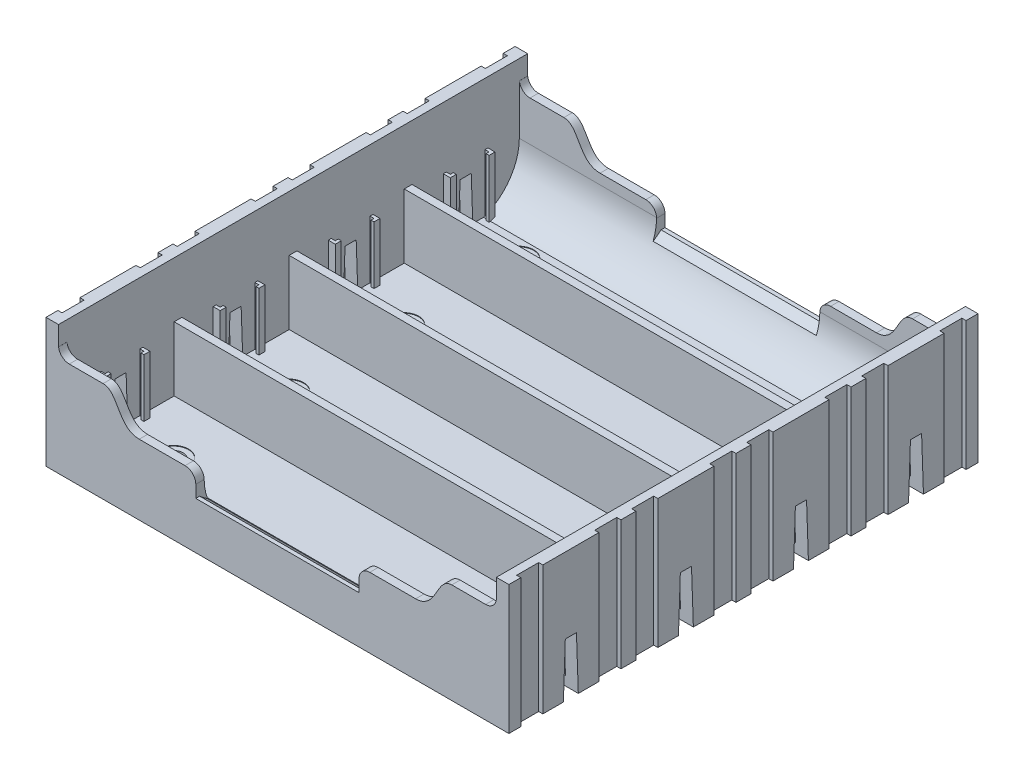
SolidWorks part; units mm, degrees
ref_plane "Спереди" through (0, 0, 0) normal (0, 0, 1) x (1, 0, 0)
ref_plane "Сверху" through (0, 0, 0) normal (0, 1, 0) x (1, 0, 0)
ref_plane "Справа" through (0, 0, 0) normal (1, 0, 0) x (0, 0, -1)
sketch "Эскиз1" plane through (0, 0, 0) normal (0, 0, 1) x (1, 0, 0)
  line L0 (-36.725, 0) -> (36.725, 0)
  line L1 (-36.725, 0) -> (-36.725, 18.61)
  line L2 (-36.725, 18.61) -> (-34.925, 18.61) construction
  line L3 (-34.925, 16.81) -> (-29.245, 16.81)
  line L4 (-23.185, 11.76) -> (-15.495, 11.76)
  line L5 (-15.495, 11.76) -> (-15.495, 9.96) construction
  line L6 (-13.695, 9.96) -> (-13.695, 7.9)
  line L7 (-13.695, 7.9) -> (13.695, 7.9)
  line L8 (0, 7.9) -> (0, 0) construction
  line L9 (36.725, 0) -> (36.725, 18.61)
  line L10 (34.925, 16.81) -> (29.245, 16.81)
  line L11 (23.185, 11.76) -> (15.495, 11.76)
  line L12 (13.695, 9.96) -> (13.695, 7.9)
  arc A0 (-36.725, 18.61) -> (-34.925, 16.81) centre (-34.925, 18.61) ccw
  arc A1 (-15.495, 11.76) -> (-13.695, 9.96) centre (-15.495, 9.96) cw
  arc A2 (36.725, 18.61) -> (34.925, 16.81) centre (34.925, 18.61) cw
  arc A3 (15.495, 11.76) -> (13.695, 9.96) centre (15.495, 9.96) ccw
  spline S0 degree 3 poles (-29.245, 16.81) (-26.6157, 16.7858) (-26.8128, 11.7896) (-23.185, 11.76) knots 0 0 0 0 1 1 1 1
  spline S1 degree 3 poles (29.245, 16.81) (26.6157, 16.7858) (26.8128, 11.7896) (23.185, 11.76) knots 0 0 0 0 1 1 1 1
  point P4 (0, 0)
  dimension "D1" = 73.45
  dimension "D2" = 18.61
  dimension "D3" = 1.8
  dimension "D4" = 5.68
  dimension "D5" = 7.69
  dimension "D6" = 5.05
  dimension "D7" = 6.06
  dimension "D8" = 1.8
  dimension "D9" = 2.06
extrude "Бобышка-Вытянуть1" add sketch "Эскиз1" against normal blind 10.4
sketch "Эскиз2" plane through (-36.725, 0, 0) normal (-1, 0, 0) x (0, 0, 1)
  line L5 (0, 18.61) -> (0, 0) construction
  line L42 (0, 1.5749) -> (-3, 1.5749)
  line L43 (-3, -0.9251) -> (-3, 1.5749) construction
  line L44 (-9, 10.0602) -> (-9, 18.4052)
  line L45 (-9, 18.4052) -> (-10.7657, 18.4052)
  line L46 (-10.7657, 18.4052) -> (-10.7657, 19.9735)
  line L47 (-10.7657, 19.9735) -> (0, 19.9735)
  line L48 (0, 19.9735) -> (0, 1.5749)
  arc A3 (-9, 10.0602) -> (-3, 1.5749) centre (0, 10.0602) ccw
  dimension "D1" = 3
  dimension "D3" = 9
  dimension "D2" = 2.5
  dimension "D5" = 3
extrude "Вырез-Вытянуть1" cut sketch "Эскиз2" against normal through all
sketch "Эскиз3" plane through (-36.725, 0, 0) normal (-1, 0, 0) x (0, 0, 1)
  line L0 (0, 0) -> (-10.4, 0) construction
  line L1 (0, 0) -> (0, 19.1837) construction
  line L3 (-10.4, 0) -> (-5.2, 0) construction
  circle A0 centre (0, 19.3) radius 15
  dimension "D1" = 19.3
extrude "Вырез-Вытянуть2" cut sketch "Эскиз3" against normal up to surface (27.39 mm away) from surface at -23.03 contours A0 up to face at (13.695, 8.9281, -9.649) starting at face at (-13.695, 8.9281, -9.649)
mirror "Зеркальное отражение6" [suppressed]
sketch "Эскиз4" plane through (0, 0, 0) normal (0, -1, 0) x (1, 0, 0)
  line L0 (36.725, 0) -> (-36.725, 0) construction
  line L8 (-36.05, -3.25) -> (-36.05, -2.75) construction
  line L9 (36.05, 2.75) -> (36.05, 3.25) construction
  line L10 (36.05, -3.25) -> (36.05, -2.75) construction
  line L11 (36.725, -10.4) -> (36.725, 0) construction
  line L12 (-36.05, -3.25) -> (-37.25, -3.25)
  line L13 (-36.05, -3.25) -> (-36.05, -2.75)
  line L14 (-36.05, 3.25) -> (-37.25, 3.25)
  line L17 (36.05, 2.75) -> (36.05, 3.25)
  line L18 (-35.55, -3.75) -> (-35.55, -2.75)
  line L19 (-37.25, 3.75) -> (-35.55, 3.75)
  line L21 (-37.25, -3.75) -> (-35.55, -3.75)
  line L23 (37.25, -3.75) -> (37.25, -3.25)
  line L24 (35.55, -2.75) -> (36.05, -2.75)
  line L25 (-35.55, 3.75) -> (-35.55, 2.75)
  line L26 (-37.25, 3.25) -> (-37.25, 3.75)
  line L27 (-35.55, 2.75) -> (-36.05, 2.75)
  line L28 (-35.55, -2.75) -> (-36.05, -2.75)
  line L29 (-37.25, -3.75) -> (-37.25, -3.25)
  line L31 (-36.05, 2.75) -> (-36.05, 3.25)
  line L32 (-36.05, 2.75) -> (-36.05, 3.25) construction
  line L33 (35.55, 2.75) -> (36.05, 2.75)
  line L34 (37.25, 3.25) -> (37.25, 3.75)
  line L35 (35.55, 3.75) -> (35.55, 2.75)
  line L36 (37.25, -3.75) -> (35.55, -3.75)
  line L37 (37.25, 3.75) -> (35.55, 3.75)
  line L38 (35.55, -3.75) -> (35.55, -2.75)
  line L39 (36.05, 3.25) -> (37.25, 3.25)
  line L41 (36.05, -3.25) -> (37.25, -3.25)
  line L42 (36.05, -3.25) -> (36.05, -2.75)
  point P0 (35.8, 2.75)
  point P5 (0, 0)
  point P31 (0, 0)
  dimension "D1" = 5.5
  dimension "D2" = 72.1
  dimension "D3" = 0.5
  dimension "D4" = 0.5
  dimension "D5" = 2.75
  dimension "D6" = 0.5
  dimension "D7" = 0.5
  dimension "D8" = 0.675
sketch "Эскиз5" plane through (0, 0, 0) normal (0, -1, 0) x (1, 0, 0)
  line L0 (36.725, 10.4) -> (36.725, -10.4)
  line L5 (36.725, -10.4) -> (38.825, -10.4)
  line L6 (36.725, 10.4) -> (38.825, 10.4)
  line L12 (38.825, 10.4) -> (38.825, 8.4)
  line L14 (38.125, 8.4) -> (38.125, 4.7)
  line L15 (38.825, 4.7) -> (38.125, 4.7)
  line L16 (38.825, -4.7) -> (38.125, -4.7)
  line L17 (38.125, -8.4) -> (38.825, -8.4)
  line L18 (38.125, 8.4) -> (38.825, 8.4)
  line L20 (38.125, -4.7) -> (38.125, -8.4)
  line L21 (-38.125, 8.4) -> (-38.825, 8.4)
  line L22 (38.825, -8.4) -> (38.825, -10.4)
  line L23 (38.825, 4.7) -> (38.825, -4.7)
  line L24 (-38.825, 4.7) -> (-38.125, 4.7)
  line L25 (-38.825, -4.7) -> (-38.125, -4.7)
  line L26 (-38.125, -8.4) -> (-38.825, -8.4)
  line L27 (-38.825, -10.4) -> (-38.125, -10.4)
  line L28 (-36.725, -10.4) -> (-38.125, -10.4)
  line L29 (-38.825, -8.4) -> (-38.825, -10.4)
  line L30 (-38.125, -4.7) -> (-38.125, -8.4)
  line L31 (-38.825, 4.7) -> (-38.825, -4.7)
  line L32 (-38.125, 8.4) -> (-38.125, 4.7)
  line L33 (-38.825, 10.4) -> (-38.825, 8.4)
  line L34 (-36.725, 10.4) -> (-38.825, 10.4)
  line L35 (-36.725, 10.4) -> (-36.725, -10.4)
  point P4 (0, 0)
  point P12 (38.475, 0)
  point P15 (38.825, 0)
  dimension "D1" = 2.1
  dimension "D3" = 9.4
sketch "Эскиз17" plane through (0, 0, 0) normal (0, 0, 1) x (1, 0, 0)
  line L1 (-36.725, 1.5749) -> (36.725, 1.5749)
  line L2 (-36.725, 1.5749) -> (-36.725, 0)
  line L3 (-36.725, 0) -> (36.725, 0)
  line L4 (36.725, 1.5749) -> (36.725, 0)
  line L5 (-36.725, 1.5749) -> (36.725, 0) construction
  line L6 (-36.725, 0) -> (36.725, 1.5749) construction
  point P4 (0, 0.7875)
extrude "Бобышка-Вытянуть12" add sketch "Эскиз17" along normal blind 28.95
mirror "Зеркальное отражение7" about plane through (0, 0, 28.95) normal (0, 0, 1) of bodies 139
extrude "Бобышка-Вытянуть8" add sketch "Эскиз5" against normal blind 21.65
extrude "Бобышка-Вытянуть9" add sketch "Эскиз4" against normal blind 11.28
sketch "Эскиз16" plane through (0, 0, 0) normal (0, -1, 0) x (1, 0, 0)
  line L0 (-38.825, 0) -> (38.825, 0) construction
  line L5 (-36.05, 1.25) -> (-39.4409, 1.25)
  line L9 (-36.05, -1.25) -> (-36.05, 1.25)
  line L10 (-39.4409, 1.25) -> (-39.4409, -1.25)
  line L11 (-39.4409, -1.25) -> (-36.05, -1.25)
  line L12 (39.4409, 1.25) -> (39.4409, -1.25)
  line L13 (36.05, 1.25) -> (39.4409, 1.25)
  line L14 (36.05, -1.25) -> (36.05, 1.25)
  line L15 (39.4409, -1.25) -> (36.05, -1.25)
  line L16 (38.825, -4.7) -> (38.825, 4.7) construction
  line L18 (-38.825, 0) -> (38.825, 0) construction
  point P0 (0, 0)
  point P17 (0, 0)
  dimension "D1" = 2.5
  dimension "D2" = 72.1
  dimension "D3" = 3.3909
  dimension "D4" = 2.775
  dimension "D5" = 3.3909
  dimension "D6" = 2.5
sketch "Эскиз18" plane through (0, 0, 0) normal (0, -1, 0) x (1, 0, 0)
  line L0 (-27.81, 0) -> (27.81, 0) construction
  circle A0 centre (-27.81, 0) radius 1.6
  circle A1 centre (27.81, 0) radius 1.6
  point P4 (0, 0)
  dimension "D1" = 55.62
extrude "Вырез-Вытянуть5" cut sketch "Эскиз16" against normal blind 9 draft 2
extrude "Вырез-Вытянуть6" cut sketch "Эскиз18" against normal blind 9
sketch "Эскиз19" [suppressed] plane through (0, 0, 0) normal (0, -1, 0) x (1, 0, 0)
  line L0 (-27.81, 0) -> (27.81, 0) construction
  circle A0 centre (27.81, 0) radius 1.6
  circle A1 centre (-27.81, 0) radius 1.6
  point P4 (0, 0)
  point P7 (-27.81, 0)
  dimension "D1" = 55.62
extrude "Вырез-Вытянуть7" [suppressed] cut sketch "Эскиз19" against normal blind 9
sketch "Эскиз20" [suppressed] plane through (0, 1.5749, 0) normal (0, 1, 0) x (1, 0, 0)
  circle A0 centre (27.81, 0) radius 2.5
  circle A1 centre (-27.81, 0) radius 2.5
extrude "Вырез-Вытянуть8" [suppressed] cut sketch "Эскиз20" against normal blind 0.1
sketch "Эскиз21" plane through (0, 1.5749, 0) normal (0, 1, 0) x (1, 0, 0)
  circle A0 centre (27.81, 0) radius 2.5
  circle A1 centre (-27.81, 0) radius 2.5
extrude "Вырез-Вытянуть9" cut sketch "Эскиз21" against normal blind 0.1
sketch "Эскиз22" [suppressed] plane through (0, 0, 0) normal (0, -1, 0) x (-1, 0, 0)
  line L0 (-38.825, 0) -> (38.825, 0) construction
  line L5 (-36.05, 1.25) -> (-39.4409, 1.25)
  line L9 (-36.05, -1.25) -> (-36.05, 1.25)
  line L10 (-39.4409, 1.25) -> (-39.4409, -1.25)
  line L11 (-39.4409, -1.25) -> (-36.05, -1.25)
  line L12 (39.4409, 1.25) -> (39.4409, -1.25)
  line L13 (36.05, 1.25) -> (39.4409, 1.25)
  line L14 (36.05, -1.25) -> (36.05, 1.25)
  line L15 (39.4409, -1.25) -> (36.05, -1.25)
  line L16 (38.825, -4.7) -> (38.825, 4.7) construction
  line L18 (-38.825, 0) -> (38.825, 0) construction
  line L19 (-38.825, 4.7) -> (-38.825, -4.7) construction
  point P0 (0, 0)
  point P17 (0, 0)
  dimension "D1" = 2.5
  dimension "D2" = 72.1
  dimension "D3" = 3.3909
  dimension "D4" = 2.775
  dimension "D5" = 3.3909
  dimension "D6" = 2.5
  dimension "D7" = 2.775
extrude "Вырез-Вытянуть10" [suppressed] cut sketch "Эскиз22" against normal blind 9 draft 2
pattern_linear "Линейный массив1" count 4 spacing 19.3 along (0, 0, 1) of "Вырез-Вытянуть9", "Вырез-Вытянуть6", "Вырез-Вытянуть5", "Бобышка-Вытянуть9", "Бобышка-Вытянуть8"
sketch "Эскиз13" plane through (0, 21.65, 0) normal (0, 1, 0) x (1, 0, 0)
  line L0 (-38.825, -9.65) -> (-36.725, -9.65) construction
  line L5 (-38.825, -10.9) -> (-38.825, -8.4) construction
  line L6 (-36.725, 10.4) -> (-36.725, -68.3) construction
  line L7 (38.125, -10.3058) -> (38.4945, -10.3058) construction
  line L9 (38.125, -9.0058) -> (38.4945, -9.0058) construction
  line L11 (38.4945, -9.0058) -> (-38.3934, -9.0058)
  line L12 (38.4945, -9.0058) -> (38.4945, -10.3058)
  line L13 (38.4945, -10.3058) -> (-38.3934, -10.3058)
  line L14 (-38.3934, -9.0058) -> (-38.3934, -10.3058)
  line L15 (38.4945, -9.0058) -> (-38.3934, -10.3058) construction
  line L16 (38.4945, -10.3058) -> (-38.3934, -9.0058) construction
  point P14 (0.0505, -9.6558)
extrude "Бобышка-Вытянуть10" add sketch "Эскиз13" against normal up to surface (10.7751 mm away) from offset 9.3 up to face at (27.81, 1.5749, 60.4) offset against normal yes
pattern_linear "Линейный массив2" [suppressed] count 2 spacing 19.3
pattern_linear "Линейный массив3" [suppressed] count 3 spacing 19.3
pattern_linear "Линейный массив4" count 3 spacing 19.3 along (0, 0, 1) of "Бобышка-Вытянуть10"
equation "\"D\"=0.8"
